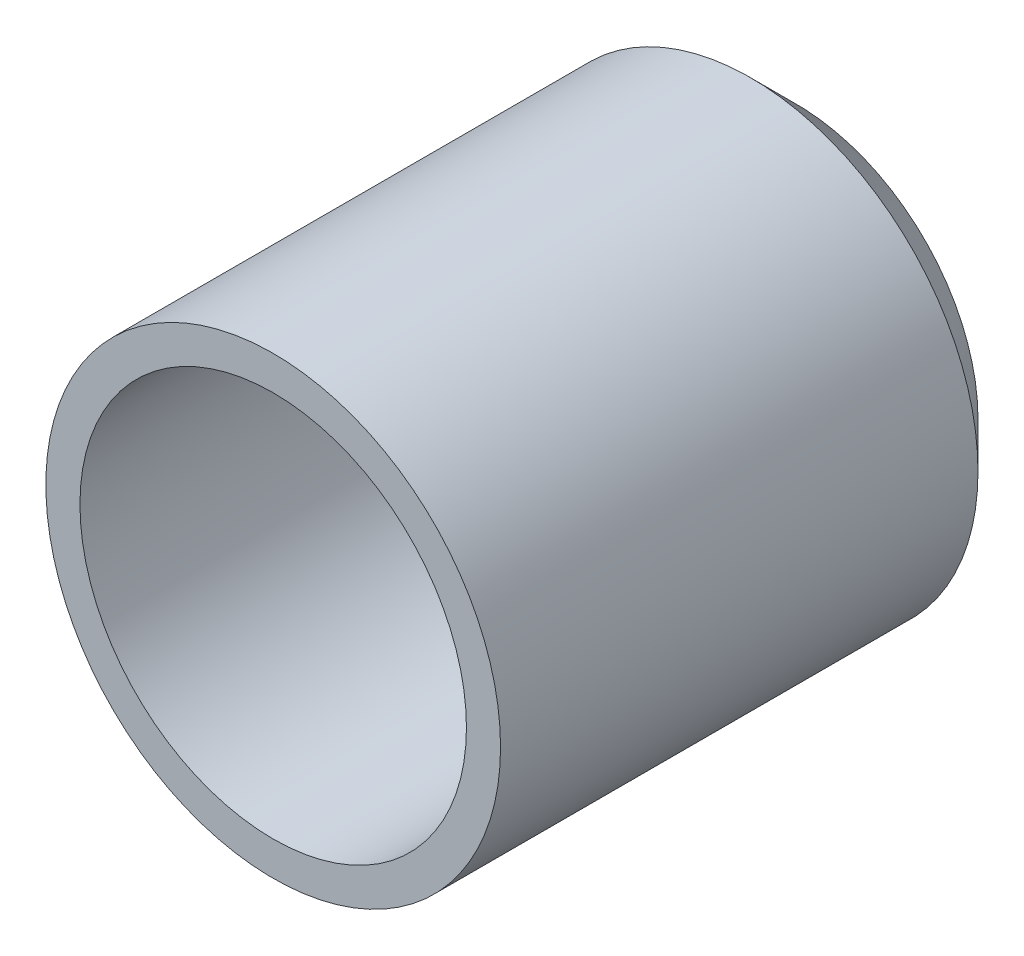
SolidWorks part; units mm, degrees
ref_plane "Alzado" through (0, 0, 0) normal (0, 0, 1) x (1, 0, 0)
ref_plane "Planta" through (0, 0, 0) normal (0, 1, 0) x (1, 0, 0)
ref_plane "Vista lateral" through (0, 0, 0) normal (1, 0, 0) x (0, 0, -1)
sketch "Croquis1" plane through (0, 0, 0) normal (0, 0, 1) x (1, 0, 0)
  circle A0 centre (0, 0) radius 10
  dimension "D1" = 20
extrude "Saliente-Extruir1" add sketch "Croquis1" against normal blind 23
chamfer "Chaflán1" distance 2 angle 45 1 edges at (10, 0, -23)
sketch "Croquis2" plane through (0, 0, 0) normal (0, 0, 1) x (1, 0, 0)
  circle A0 centre (0, 0) radius 8.5
  dimension "D1" = 17
extrude "Cortar-Extruir1" cut sketch "Croquis2" against normal blind 15
